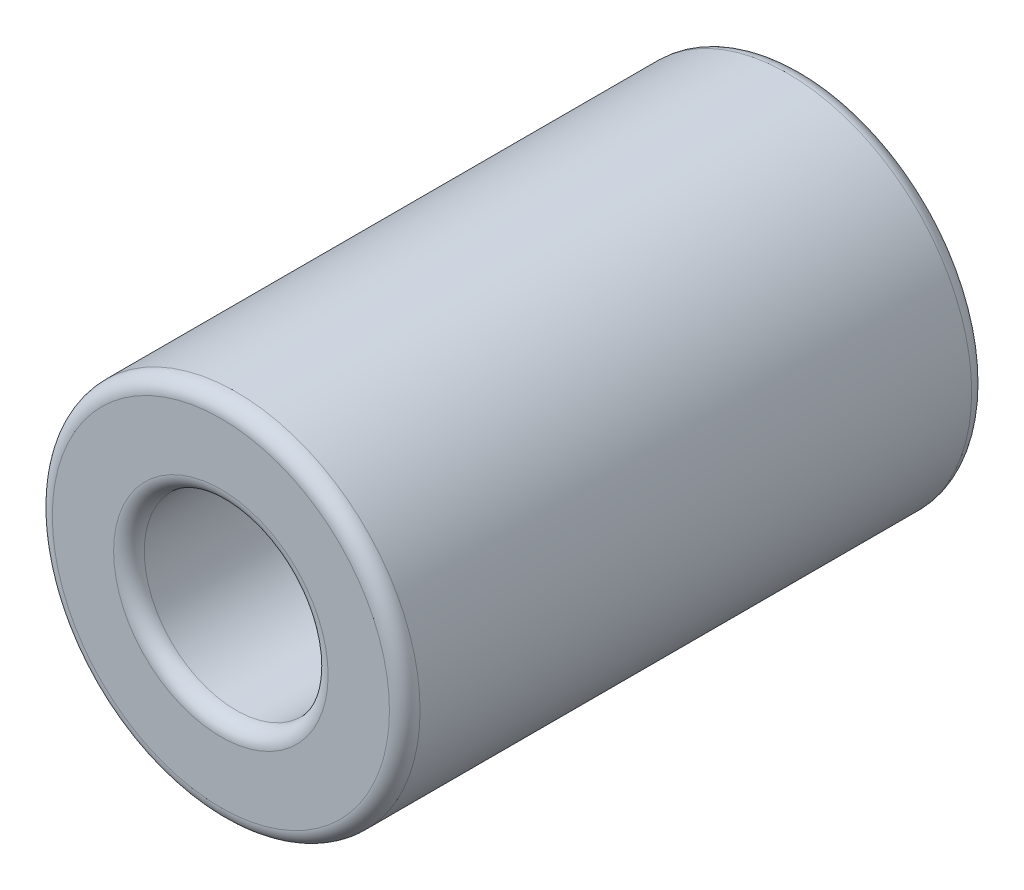
SolidWorks part; units mm, degrees
material "AISI 1015 钢，冷拔 (SS)"
ref_plane "前视基准面" through (0, 0, 0) normal (0, 0, 1) x (1, 0, 0)
ref_plane "上视基准面" through (0, 0, 0) normal (0, 1, 0) x (1, 0, 0)
ref_plane "右视基准面" through (0, 0, 0) normal (1, 0, 0) x (0, 0, -1)
other "Configuration Table"
sketch "草图1" plane through (0, 0, 0) normal (0, 0, 1) x (1, 0, 0)
  circle A0 centre (0, 0) radius 3
  circle A1 centre (0, 0) radius 6
  dimension "D1" = 6
  dimension "D2" = 12
extrude "凸台-拉伸1" add sketch "草图1" along normal blind 19
fillet "圆角1" radius 0.5 4 edges at (6, 0, 0) (6, 0, 19) (3, 0, 0) (3, 0, 19)
